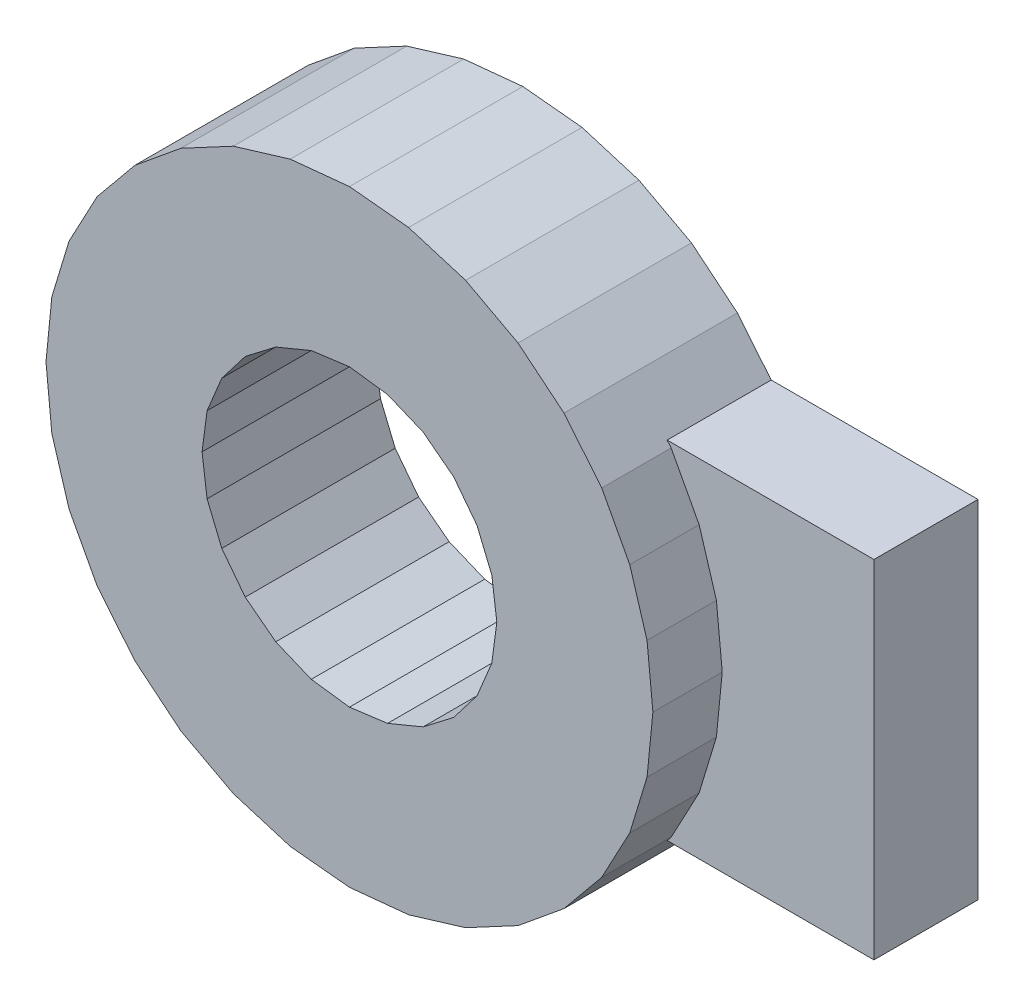
SolidWorks part; units mm, degrees
ref_plane "Front Plane" through (0, 0, 0) normal (0, 0, 1) x (1, 0, 0)
ref_plane "Top Plane" through (0, 0, 0) normal (0, 1, 0) x (1, 0, 0)
ref_plane "Right Plane" through (0, 0, 0) normal (1, 0, 0) x (0, 0, -1)
ref_plane "Plane1" through (0, 0, 2) normal (0, 0, 1) x (1, 0, 0)
sketch "Sketch1" plane through (0, 0, 2) normal (0, 0, 1) x (1, 0, 0)
  line L0 (1.9445, 2.9101) -> (1.3394, 3.2336)
  line L1 (1.3394, 3.2336) -> (0.6828, 3.4327)
  line L2 (0.6828, 3.4327) -> (0, 3.5)
  line L3 (0, 3.5) -> (-0.6828, 3.4327)
  line L4 (-0.6828, 3.4327) -> (-1.3394, 3.2336)
  line L5 (-1.3394, 3.2336) -> (-1.9445, 2.9101)
  line L6 (-1.9445, 2.9101) -> (-2.4749, 2.4749)
  line L7 (-2.4749, 2.4749) -> (-2.9101, 1.9445)
  line L8 (-2.9101, 1.9445) -> (-3.2336, 1.3394)
  line L9 (-3.2336, 1.3394) -> (-3.4327, 0.6828)
  line L10 (-3.4327, 0.6828) -> (-3.5, 0)
  line L11 (-3.5, 0) -> (-3.4327, -0.6828)
  line L12 (-3.4327, -0.6828) -> (-3.2336, -1.3394)
  line L13 (-3.2336, -1.3394) -> (-2.9101, -1.9445)
  line L14 (-2.9101, -1.9445) -> (-2.4749, -2.4749)
  line L15 (-2.4749, -2.4749) -> (-1.9445, -2.9101)
  line L16 (-1.9445, -2.9101) -> (-1.3394, -3.2336)
  line L17 (-1.3394, -3.2336) -> (-0.6828, -3.4327)
  line L18 (-0.6828, -3.4327) -> (0, -3.5)
  line L19 (0, -3.5) -> (0.6828, -3.4327)
  line L20 (0.6828, -3.4327) -> (1.3394, -3.2336)
  line L21 (1.3394, -3.2336) -> (1.9445, -2.9101)
  line L22 (1.9445, -2.9101) -> (2.4749, -2.4749)
  line L23 (2.4749, -2.4749) -> (2.9101, -1.9445)
  line L24 (2.9101, -1.9445) -> (3.2336, -1.3394)
  line L25 (3.2336, -1.3394) -> (3.4327, -0.6828)
  line L26 (3.4327, -0.6828) -> (3.5, 0)
  line L27 (3.5, 0) -> (3.4327, 0.6828)
  line L28 (3.4327, 0.6828) -> (3.2336, 1.3394)
  line L29 (3.2336, 1.3394) -> (2.9101, 1.9445)
  line L30 (2.9101, 1.9445) -> (2.4749, 2.4749)
  line L31 (2.4749, 2.4749) -> (1.9445, 2.9101)
extrude "Boss-Extrude1" add sketch "Sketch1" against normal blind 0.8
sketch "Sketch2" plane through (0, 0, 1.2) normal (0, 0, -1) x (-1, 0, 0)
  line L0 (-5.25, -2) -> (-5.25, 2)
  line L1 (-5.25, 2) -> (-2.8646, 2)
  line L2 (-2.8646, 2) -> (-2.4749, 2.4749)
  line L3 (-2.4749, 2.4749) -> (-1.9445, 2.9101)
  line L4 (-1.9445, 2.9101) -> (-1.3394, 3.2336)
  line L5 (-1.3394, 3.2336) -> (-0.6828, 3.4327)
  line L6 (-0.6828, 3.4327) -> (0, 3.5)
  line L7 (0, 3.5) -> (0.6828, 3.4327)
  line L8 (0.6828, 3.4327) -> (1.3394, 3.2336)
  line L9 (1.3394, 3.2336) -> (1.9445, 2.9101)
  line L10 (1.9445, 2.9101) -> (2.4749, 2.4749)
  line L11 (2.4749, 2.4749) -> (2.9101, 1.9445)
  line L12 (2.9101, 1.9445) -> (3.2336, 1.3394)
  line L13 (3.2336, 1.3394) -> (3.4327, 0.6828)
  line L14 (3.4327, 0.6828) -> (3.5, 0)
  line L15 (3.5, 0) -> (3.4327, -0.6828)
  line L16 (3.4327, -0.6828) -> (3.2336, -1.3394)
  line L17 (3.2336, -1.3394) -> (2.9101, -1.9445)
  line L18 (2.9101, -1.9445) -> (2.4749, -2.4749)
  line L19 (2.4749, -2.4749) -> (1.9445, -2.9101)
  line L20 (1.9445, -2.9101) -> (1.3394, -3.2336)
  line L21 (1.3394, -3.2336) -> (0.6828, -3.4327)
  line L22 (0.6828, -3.4327) -> (0, -3.5)
  line L23 (0, -3.5) -> (-0.6828, -3.4327)
  line L24 (-0.6828, -3.4327) -> (-1.3394, -3.2336)
  line L25 (-1.3394, -3.2336) -> (-1.9445, -2.9101)
  line L26 (-1.9445, -2.9101) -> (-2.4749, -2.4749)
  line L27 (-2.4749, -2.4749) -> (-2.8646, -2)
  line L28 (-2.8646, -2) -> (-5.25, -2)
extrude "Boss-Extrude2" add sketch "Sketch2" along normal blind 1.2
sketch "Sketch3" plane through (0, 0, 0) normal (0, 0, -1) x (-1, 0, 0)
  line L0 (-1.4722, 0.85) -> (-1.6421, 0.44)
  line L1 (-1.6421, 0.44) -> (-1.7, 0)
  line L2 (-1.7, 0) -> (-1.6421, -0.44)
  line L3 (-1.6421, -0.44) -> (-1.4722, -0.85)
  line L4 (-1.4722, -0.85) -> (-1.2021, -1.2021)
  line L5 (-1.2021, -1.2021) -> (-0.85, -1.4722)
  line L6 (-0.85, -1.4722) -> (-0.44, -1.6421)
  line L7 (-0.44, -1.6421) -> (0, -1.7)
  line L8 (0, -1.7) -> (0.44, -1.6421)
  line L9 (0.44, -1.6421) -> (0.85, -1.4722)
  line L10 (0.85, -1.4722) -> (1.2021, -1.2021)
  line L11 (1.2021, -1.2021) -> (1.4722, -0.85)
  line L12 (1.4722, -0.85) -> (1.6421, -0.44)
  line L13 (1.6421, -0.44) -> (1.7, 0)
  line L14 (1.7, 0) -> (1.6421, 0.44)
  line L15 (1.6421, 0.44) -> (1.4722, 0.85)
  line L16 (1.4722, 0.85) -> (1.2021, 1.2021)
  line L17 (1.2021, 1.2021) -> (0.85, 1.4722)
  line L18 (0.85, 1.4722) -> (0.44, 1.6421)
  line L19 (0.44, 1.6421) -> (0, 1.7)
  line L20 (0, 1.7) -> (-0.44, 1.6421)
  line L21 (-0.44, 1.6421) -> (-0.85, 1.4722)
  line L22 (-0.85, 1.4722) -> (-1.2021, 1.2021)
  line L23 (-1.2021, 1.2021) -> (-1.4722, 0.85)
extrude "Cut-Extrude1" cut sketch "Sketch3" against normal through all
